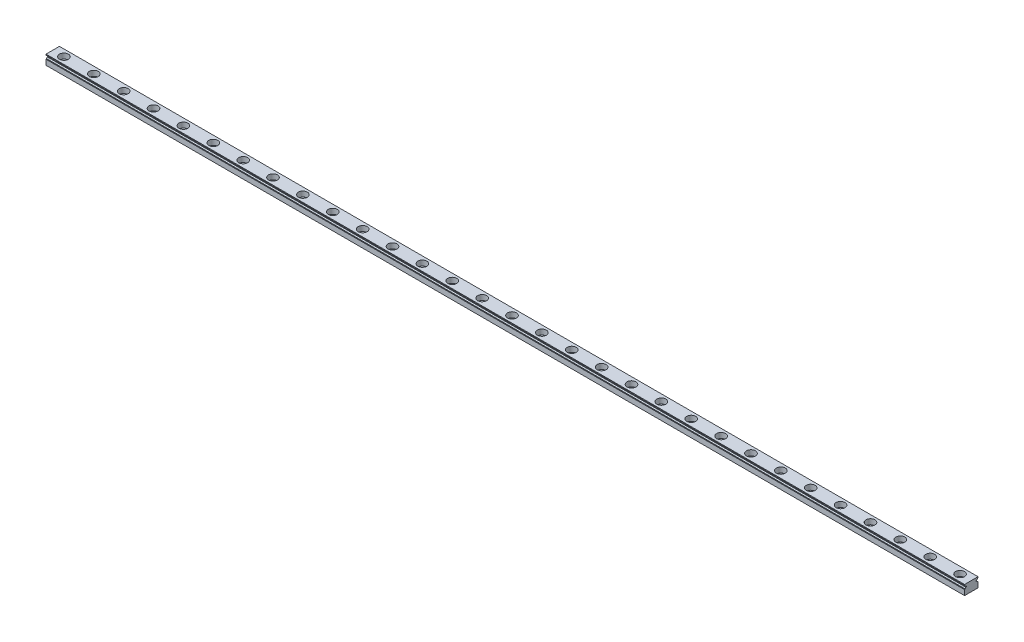
SolidWorks part; units mm, degrees
ref_plane "Plan de face" through (0, 0, 0) normal (0, 0, 1) x (1, 0, 0)
ref_plane "Plan de dessus" through (0, 0, 0) normal (0, 1, 0) x (1, 0, 0)
ref_plane "Plan de droite" through (0, 0, 0) normal (1, 0, 0) x (0, 0, -1)
other "L"
sketch "Esquisse1" plane through (0, 0, 0) normal (1, 0, 0) x (0, 0, -1)
  line L0 (0, 0) -> (0, 10.8057) construction
  line L1 (-4.5, 0) -> (4.5, 0)
  line L2 (4.5, 0) -> (4.5, 3.5)
  line L3 (4.5, 3.5) -> (3.6, 4.4)
  line L4 (3.6, 4.4) -> (3.3, 4.4)
  line L5 (3.3, 4.4) -> (3.3, 5)
  line L6 (4.5, 5.9) -> (3.6, 5)
  line L7 (3.6, 5) -> (3.3, 5)
  line L8 (4.5, 5.9) -> (4.5, 6.5)
  line L9 (4.5, 6.5) -> (-4.5, 6.5)
  line L10 (3.3, 4.7) -> (8.4079, 4.7) construction
  line L11 (-4.5, 5.9) -> (-4.5, 6.5)
  line L12 (-4.5, 5.9) -> (-3.6, 5)
  line L13 (-3.6, 5) -> (-3.3, 5)
  line L14 (-3.3, 4.4) -> (-3.3, 5)
  line L15 (-3.6, 4.4) -> (-3.3, 4.4)
  line L16 (-4.5, 3.5) -> (-3.6, 4.4)
  line L17 (-4.5, 0) -> (-4.5, 3.5)
  point P18 (0, 6.5)
  dimension "D1" = 6.5
  dimension "D2" = 9
  dimension "D3" = 0.6
  dimension "D4" = 1.2
  dimension "D5" = 2.4
  dimension "D6" = 4.7
extrude "Boss.-Extru.1" add sketch "Esquisse1" along normal blind 615
sketch "Esquisse2" plane through (0, 0, 0) normal (1, 0, 0) x (0, 0, -1)
  line L0 (3.3, 5) -> (3.6, 5) construction
  line L1 (4.5, 5.9) -> (4.2, 5.9)
  line L2 (4.5, 5.9) -> (4.5, 3.5)
  line L3 (4.5, 3.5) -> (4.2, 3.5)
  line L4 (4.2, 5.9) -> (4.2, 3.5)
  line L5 (0, 0) -> (0, 7.1139) construction
  line L6 (-4.5, 5.9) -> (-4.2, 5.9)
  line L7 (-4.5, 5.9) -> (-4.5, 3.5)
  line L8 (-4.5, 3.5) -> (-4.2, 3.5)
  line L9 (-4.2, 5.9) -> (-4.2, 3.5)
extrude "Enlèv. mat.-Extru.1" cut sketch "Esquisse2" along normal through all
hole_wizard "Chambrage pour vis à tête hexagonale M31" positions "Esquisse3" profile "Esquisse4" counterbore size "M3" standard "ISO" end condition through all
sketch "Esquisse3" plane through (0, 6.5, 0) normal (0, 1, 0) x (1, 0, 0)
  line L0 (0, 4.5) -> (0, -4.5) construction
  point P0 (7.5, 0)
  point P6 (0, 0)
  dimension "D1" = 7.5
sketch "Esquisse4" plane through (7.5, 6.5, 0) normal (1, 0, 0) x (0, 0, 1)
  line L0 (0, 0) -> (0, 6.5)
  line L1 (0, 6.5) -> (1.75, 6.5)
  line L3 (1.75, 6.5) -> (1.75, 3.5)
  line L4 (1.75, 3.5) -> (3, 3.5)
  line L5 (3, 3.5) -> (3, 0)
  line L7 (3, 0) -> (0, 0)
  line L11 (0, -6.35) -> (0, 107.95) construction
  dimension "Diamètre du perçage jusqu'au prochain" = 3.5
  dimension "Profondeur du perçage jusqu'au prochain" = 6.5
  dimension "Diamètre du chambrage" = 6
  dimension "Profondeur du chambrage" = 3.5
pattern_linear "Répétition linéaire1" count 31 spacing 20 along (1, 0, 0) of "Chambrage pour vis à tête hexagonale M31"
ref_plane "SYM" through (300, 0, 0) normal (-1, 0, 0) x (0, 0, 1)
move or copy body "Corps-Déplacer/Copier1" [suppressed] bodies to move or copy 104
equation "\"D1@SYM\"=\"D1@Boss.-Extru.1\"/2"
